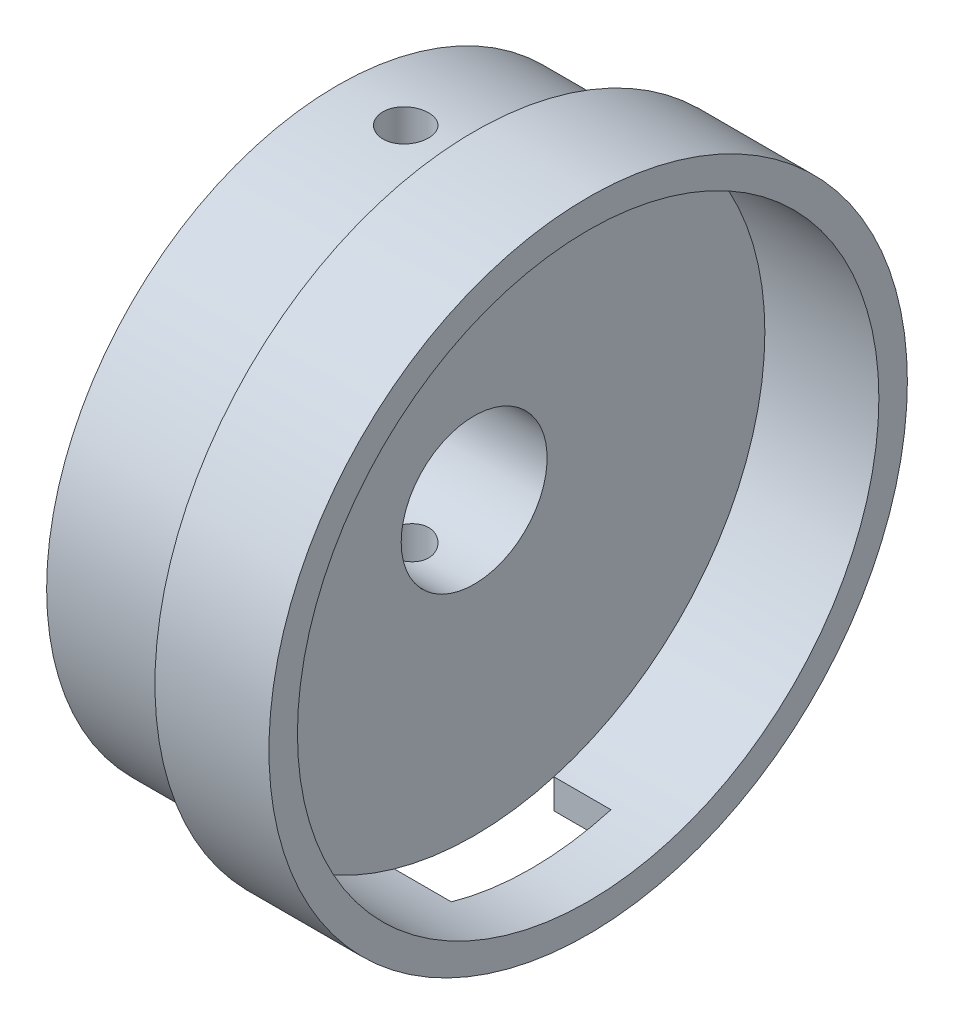
SolidWorks part; units mm, degrees
ref_plane "前视基准面" through (0, 0, 0) normal (0, 0, 1) x (1, 0, 0)
ref_plane "上视基准面" through (0, 0, 0) normal (0, 1, 0) x (1, 0, 0)
ref_plane "右视基准面" through (0, 0, 0) normal (1, 0, 0) x (0, 0, -1)
other "Configuration Table"
sketch "草图1" plane through (0, 0, 0) normal (1, 0, 0) x (0, 0, -1)
  circle A0 centre (0, 0) radius 12.75
  dimension "D1" = 25.5
extrude "凸台-拉伸1" add sketch "草图1" along normal blind 6
sketch "草图2" plane through (0, 0, 0) normal (-1, 0, 0) x (0, 0, 1)
  circle A0 centre (0, 0) radius 3.2
  dimension "D1" = 6.4
extrude "切除-拉伸1" cut sketch "草图2" against normal blind 6
sketch "草图3" plane through (0, 0, 0) normal (0, 1, 0) x (1, 0, 0)
  line L0 (0, 12.75) -> (0, -12.75) construction
  circle A0 centre (3, 0) radius 1
  dimension "D1" = 2
  dimension "D2" = 3
extrude "切除-拉伸2" cut sketch "草图3" against normal up to next and the other way up to next
sketch "草图4" plane through (6, 0, 0) normal (1, 0, 0) x (0, 0, -1)
  circle A0 centre (0, 0) radius 14
  dimension "D1" = 28
extrude "凸台-拉伸2" add sketch "草图4" along normal blind 5
sketch "草图5" plane through (11, 0, 0) normal (1, 0, 0) x (0, 0, -1)
  circle A0 centre (0, 0) radius 12.75
  dimension "D1" = 25.5
extrude "切除-拉伸3" cut sketch "草图5" against normal blind 5
sketch "草图6" plane through (0, 0, 0) normal (0, 1, 0) x (1, 0, 0)
  line L0 (0, 0) -> (11, 0) construction
  line L1 (11, -14) -> (11, 14) construction
  line L2 (6, -12.75) -> (6, 12.75) construction
  line L3 (6, 3.5) -> (8.5, 3.5)
  line L4 (6, 3.5) -> (6, -3.5)
  line L5 (6, -3.5) -> (8.5, -3.5)
  line L6 (8.5, 3.5) -> (8.5, -3.5)
  dimension "D1" = 2.5
  dimension "D2" = 7
  dimension "D3" = 3.5
extrude "切除-拉伸4" cut sketch "草图6" against normal blind 16
